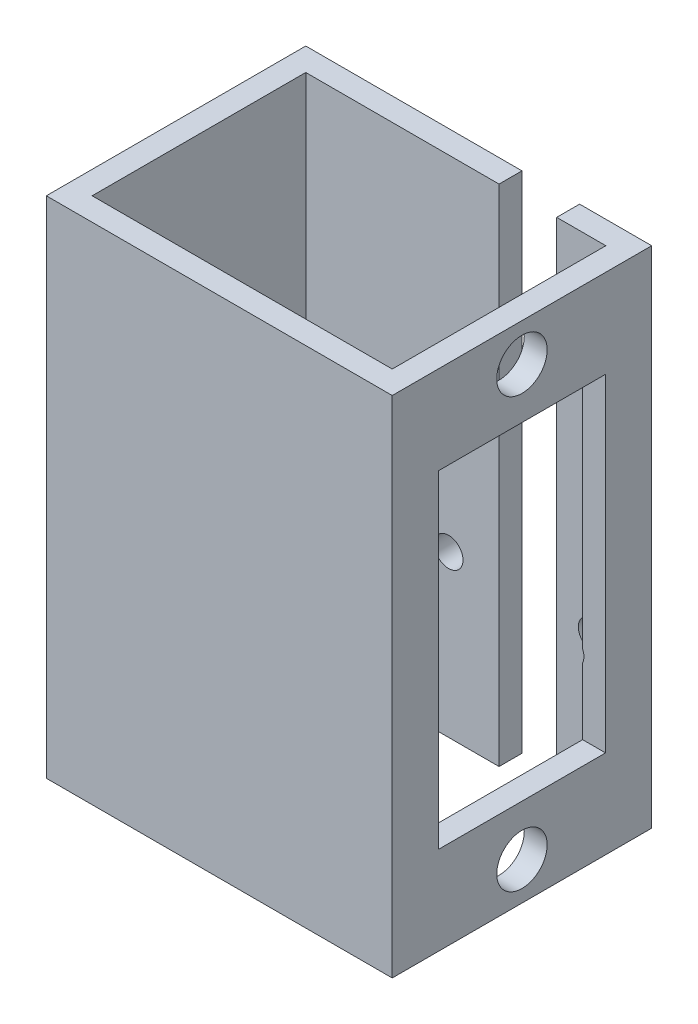
SolidWorks part; units mm, degrees
material "6061 Alloy"
ref_plane "Front Plane" through (0, 0, 0) normal (0, 0, 1) x (1, 0, 0)
ref_plane "Top Plane" through (0, 0, 0) normal (0, 1, 0) x (1, 0, 0)
ref_plane "Right Plane" through (0, 0, 0) normal (1, 0, 0) x (0, 0, -1)
sketch "Sketch1" plane through (0, 0, 0) normal (0, 1, 0) x (1, 0, 0)
  line L0 (15, 0) -> (15, -1.59)
  line L1 (0, 0) -> (15, 0)
  line L2 (0, 0) -> (0, -18)
  line L3 (0, -18) -> (24, -18)
  line L4 (24, 0) -> (24, -18)
  line L5 (1.59, -1.59) -> (15, -1.59)
  line L6 (1.59, -1.59) -> (1.59, -16.41)
  line L7 (1.59, -16.41) -> (22.41, -16.41)
  line L8 (22.41, -1.59) -> (22.41, -16.41)
  line L9 (19, 0) -> (19, -1.59)
  line L10 (19, 0) -> (24, 0)
  line L11 (19, -1.59) -> (22.41, -1.59)
  point P13 (15, -0.795)
  dimension "D1" = 1.59
  dimension "D2" = 1.59
  dimension "D3" = 1.59
  dimension "D4" = 1.59
  dimension "D5" = 18
  dimension "D6" = 24
  dimension "D7" = 5
  dimension "D8" = 15
extrude "Boss-Extrude1" add sketch "Sketch1" along normal blind 35
sketch "Sketch2" plane through (24, 0, 0) normal (1, 0, 0) x (0, 0, -1)
  line L0 (-18, 35) -> (-18, 0) construction
  line L1 (-14.8, 28.875) -> (-3.2, 28.875)
  line L2 (-14.8, 28.875) -> (-14.8, 6.125)
  line L3 (-14.8, 6.125) -> (-3.2, 6.125)
  line L4 (-3.2, 28.875) -> (-3.2, 6.125)
  line L5 (-14.8, 28.875) -> (-3.2, 6.125) construction
  line L6 (-14.8, 6.125) -> (-3.2, 28.875) construction
  line L7 (-18, 0) -> (0, 0) construction
  circle A0 centre (-9, 32.375) radius 1.75
  circle A1 centre (-9, 2.625) radius 1.75
  point P0 (-9, 17.5)
  point P7 (-18, 17.5)
  point P10 (-9, 0)
  dimension "D5" = 3.5
  dimension "D1" = 22.75
  dimension "D2" = 11.6
  dimension "D3" = 3.5
  dimension "D4" = 3.5
extrude "Cut-Extrude1" cut sketch "Sketch2" against normal blind 4
sketch "Sketch3" plane through (0, 0, 0) normal (-1, 0, 0) x (0, 0, 1)
  line L0 (0, 0) -> (18, 0) construction
  circle A0 centre (9, 11.15) radius 1.25
  point P5 (9, 0)
  dimension "D2" = 2.5
  dimension "D1" = 11.15
extrude "Cut-Extrude2" cut sketch "Sketch3" against normal blind 32
sketch "Sketch4" plane through (0, 0, 0) normal (0, 0, -1) x (-1, 0, 0)
  line L0 (0, 35) -> (0, 0) construction
  line L1 (-15, 0) -> (0, 0) construction
  circle A0 centre (-11.5, 11.15) radius 1
  circle A1 centre (-21.5, 11.15) radius 1
  dimension "D4" = 2
  dimension "D5" = 2
  dimension "D1" = 11.5
  dimension "D2" = 10
  dimension "D3" = 11.15
extrude "Cut-Extrude3" cut sketch "Sketch4" against normal blind 4
